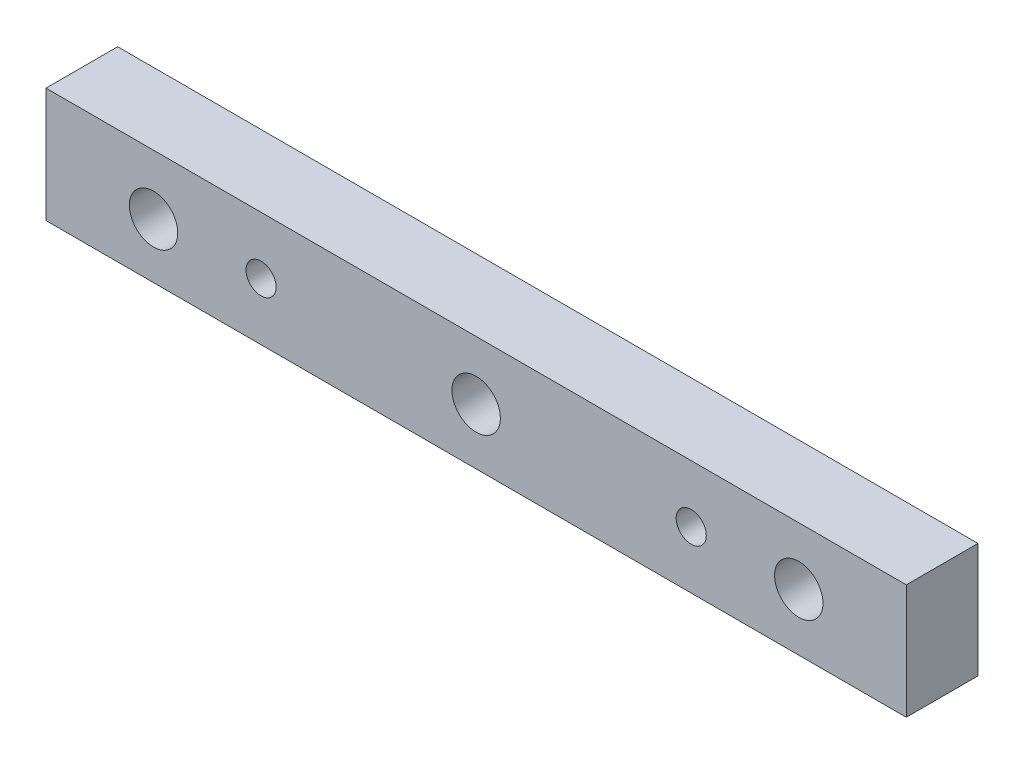
SolidWorks part; units mm, degrees
ref_plane "Alzado" through (0, 0, 0) normal (0, 0, 1) x (1, 0, 0)
ref_plane "Planta" through (0, 0, 0) normal (0, 1, 0) x (1, 0, 0)
ref_plane "Vista lateral" through (0, 0, 0) normal (1, 0, 0) x (0, 0, -1)
sketch "Croquis1" plane through (0, 0, 0) normal (0, 0, 1) x (1, 0, 0)
  line L1 (-39.4696, 11.875) -> (80.5304, 11.875)
  line L2 (-39.4696, 11.875) -> (-39.4696, -4.125)
  line L3 (-39.4696, -4.125) -> (80.5304, -4.125)
  line L4 (80.5304, 11.875) -> (80.5304, -4.125)
  dimension "D1" = 120
  dimension "D2" = 16
extrude "Saliente-Extruir1" add sketch "Croquis1" along normal blind 10
hole_wizard "Perforador para roscar para macho de roscar para M5x0.81" positions "Croquis4" profile "Croquis2" hole size "M5x0.8" standard "Ansi Metric" end condition up to next
sketch "Croquis4" plane through (0, 0, 10) normal (0, 0, 1) x (1, 0, 0)
  line L0 (-39.4696, 3.875) -> (80.5304, 3.875) construction
  line L1 (-39.4696, 11.875) -> (-39.4696, -4.125) construction
  line L2 (80.5304, -4.125) -> (80.5304, 11.875) construction
  point P0 (-9.4696, 3.875)
  point P2 (50.5304, 3.875)
  dimension "D1" = 60
  dimension "D2" = 30
sketch "Croquis2" plane through (-9.4696, 3.875, 10) normal (1, 0, 0) x (0, -1, 0)
  line L0 (0, 0) -> (0, 10)
  line L1 (0, 10) -> (2.1, 10)
  line L2 (2.1, 10) -> (2.1, 0)
  line L5 (2.1, 0) -> (0, 0)
  line L11 (0, -6.35) -> (0, 107.95) construction
  dimension "Diámetro de taladro hasta el siguiente" = 4.2
  dimension "Profundidad de taladro hasta el siguiente" = 10
hole_wizard "Taladro de margen para 1/41" positions "Croquis6" profile "Croquis5" hole size "1/4" standard "Ansi Inch" end condition up to next
sketch "Croquis6" plane through (0, 0, 10) normal (0, 0, 1) x (1, 0, 0)
  line L0 (-39.4696, 3.5082) -> (80.5304, 3.875) construction
  line L1 (-39.4696, 11.875) -> (-39.4696, -4.125) construction
  line L2 (80.5304, -4.125) -> (80.5304, 11.875) construction
  point P0 (-24.4696, 3.554)
  point P2 (20.5304, 3.6916)
  point P4 (65.5304, 3.8291)
  dimension "D1" = 15
  dimension "D2" = 15
  dimension "D3" = 60
sketch "Croquis5" plane through (-24.4696, 3.554, 10) normal (1, 0, 0) x (0, -1, 0)
  line L0 (0, 0) -> (0, 10)
  line L1 (0, 10) -> (3.3782, 10)
  line L2 (3.3782, 10) -> (3.3782, 0)
  line L5 (3.3782, 0) -> (0, 0)
  line L11 (0, -6.35) -> (0, 107.95) construction
  dimension "Diámetro de taladro hasta el siguiente" = 6.7564
  dimension "Profundidad de taladro hasta el siguiente" = 10
